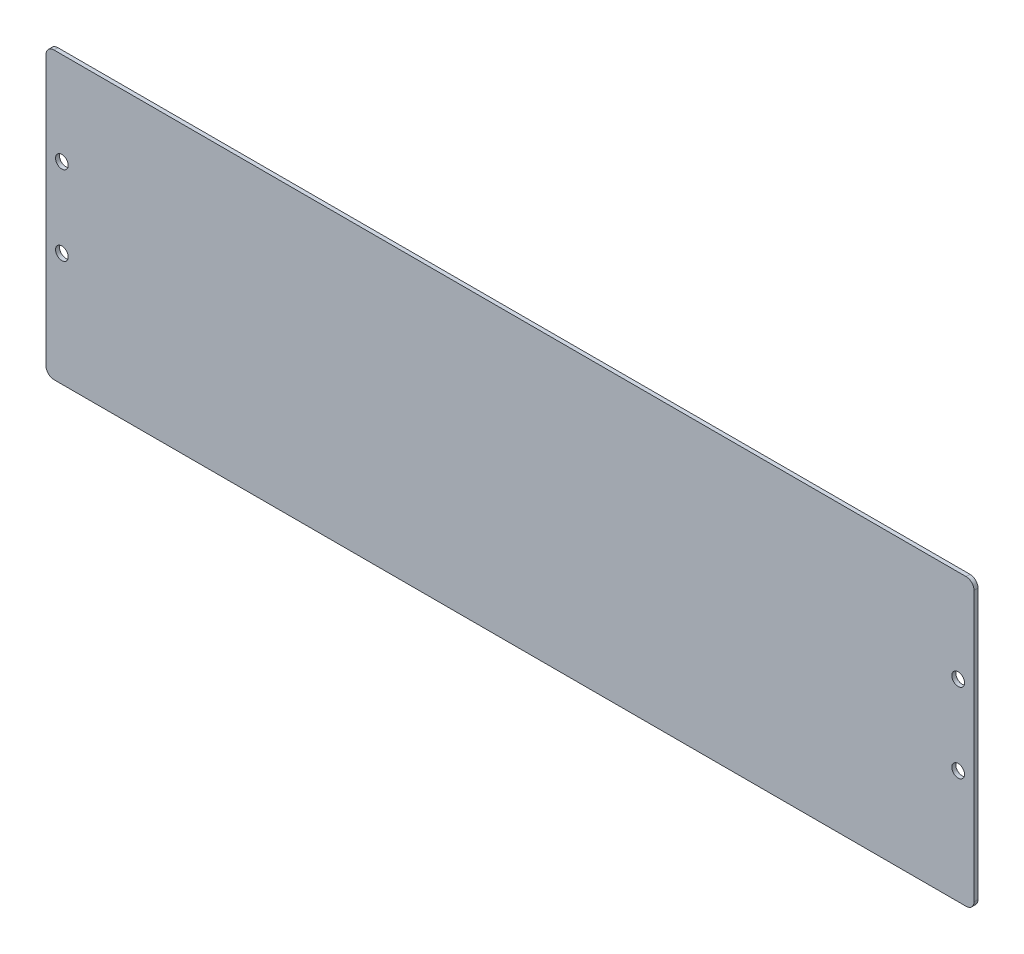
SolidWorks part; units mm, degrees
material "Thornel Mat VMA"
ref_plane "前视基准面" through (0, 0, 0) normal (0, 0, 1) x (1, 0, 0)
ref_plane "上视基准面" through (0, 0, 0) normal (0, 1, 0) x (1, 0, 0)
ref_plane "右视基准面" through (0, 0, 0) normal (1, 0, 0) x (0, 0, -1)
other "Configuration Table"
sketch "草图1" plane through (0, 0, 0) normal (0, 0, 1) x (1, 0, 0)
  line L0 (-113, 36) -> (-113, -36) construction
  line L1 (-117, -36) -> (117, -36)
  line L2 (-117, -36) -> (-117, 36)
  line L3 (-117, 36) -> (117, 36)
  line L4 (117, -36) -> (117, 36)
  line L5 (-117, -36) -> (117, 36) construction
  line L6 (-117, 36) -> (117, -36) construction
  line L7 (0, 0) -> (0, -50000) construction
  circle A0 centre (-113, 12.6) radius 1.6
  circle A1 centre (-113, -7.4) radius 1.6
  circle A2 centre (113, -7.4) radius 1.6
  circle A3 centre (113, 12.6) radius 1.6
  point P0 (0, 0)
  dimension "D3" = 20
  dimension "D4" = 3.2
  dimension "D6" = 28.6
  dimension "D1" = 234
  dimension "D2" = 72
  dimension "D5" = 4
extrude "凸台-拉伸1" add sketch "草图1" along normal blind 1
fillet "圆角1" radius 2 4 edges at (117, -36, 0.5) (-117, -36, 0.5) (117, 36, 0.5) (-117, 36, 0.5)
